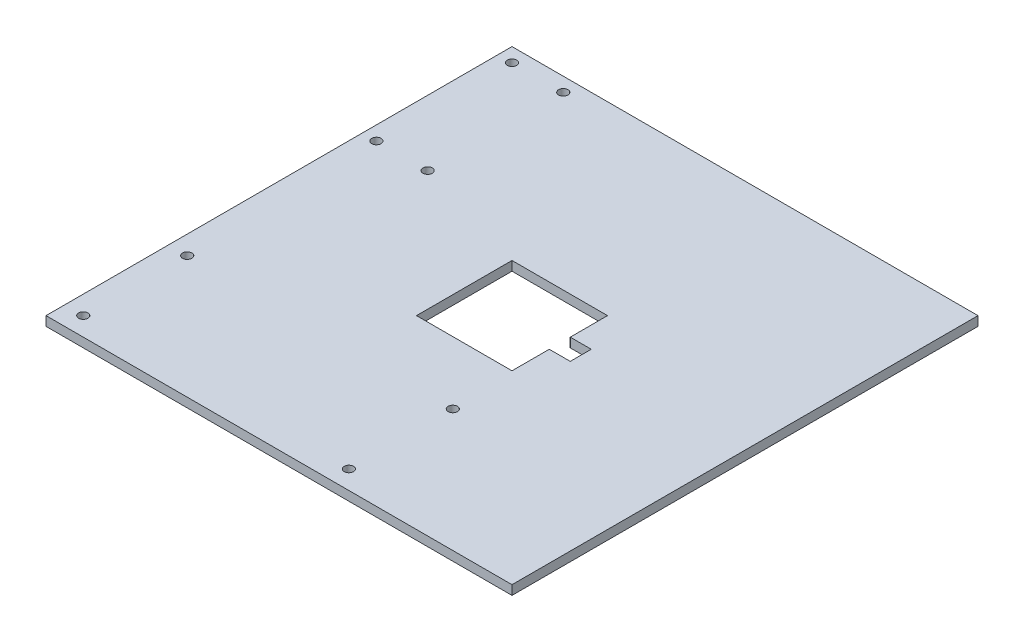
SolidWorks part; units mm, degrees
ref_plane "Front Plane" through (0, 0, 0) normal (0, 0, 1) x (1, 0, 0)
ref_plane "Top Plane" through (0, 0, 0) normal (0, 1, 0) x (1, 0, 0)
ref_plane "Right Plane" through (0, 0, 0) normal (1, 0, 0) x (0, 0, -1)
sketch "Sketch1" plane through (0, 0, 0) normal (0, 1, 0) x (1, 0, 0)
  line L1 (0, 0) -> (100, 0)
  line L2 (0, 0) -> (0, 100)
  line L3 (0, 100) -> (100, 100)
  line L4 (100, 0) -> (100, 100)
  dimension "D1" = 100
  dimension "D2" = 100
extrude "Boss-Extrude1" add sketch "Sketch1" along normal blind 2
sketch "Alignment sketch" plane through (0, 2, 0) normal (0, 1, 0) x (1, 0, 0)
  line L0 (50, 100) -> (50, 0) construction
  line L1 (100, 100) -> (0, 100) construction
  line L2 (0, 0) -> (100, 0) construction
  line L3 (0, 50) -> (100, 50) construction
  line L4 (0, 100) -> (0, 0) construction
  line L5 (100, 0) -> (100, 100) construction
  line L6 (80, 100) -> (80, 90) construction
  line L11 (0, 30.3) -> (65, 30.3) construction
  line L12 (0, 30.3) -> (0, 0) construction
  line L13 (0, 0) -> (65, 0) construction
  line L14 (65, 30.3) -> (65, 0) construction
  line L15 (17, 64.9) -> (0, 64.9) construction
  line L16 (17, 64.9) -> (17, 100) construction
  line L17 (17, 100) -> (0, 100) construction
  line L18 (0, 64.9) -> (0, 100) construction
  line L19 (80, 90) -> (20, 90) construction
  line L20 (20, 90) -> (20, 100) construction
  circle A0 centre (50, 50) radius 19.5 construction
  text T0 "Raspberry Pi Zero W"
  text T1 "Atheros"
  text T2 "Antenna"
  text T3 "Phone Attachment Zone"
  point P31 (50, 90)
  dimension "D1" = 39
  dimension "D2" = 65
  dimension "D3" = 30.3
  dimension "D4" = 35.1
  dimension "D5" = 17
  dimension "D6" = 60
  dimension "D7" = 10
sketch "Sketch3" plane through (0, 2, 0) normal (0, 1, 0) x (1, 0, 0)
  line L0 (50, 100) -> (50, 0) construction
  line L1 (39.75, 60.25) -> (60.25, 60.25)
  line L2 (39.75, 60.25) -> (39.75, 39.75)
  line L3 (39.75, 39.75) -> (60.25, 39.75)
  line L4 (60.25, 60.25) -> (60.25, 39.75)
  line L5 (0, 50) -> (100, 50) construction
  line L7 (60.25, 47.75) -> (64.75, 47.75)
  line L8 (60.25, 47.75) -> (60.25, 52.25)
  line L9 (60.25, 52.25) -> (64.75, 52.25)
  line L10 (64.75, 47.75) -> (64.75, 52.25)
  point P4 (50, 60.25)
  point P7 (50, 39.75)
  point P8 (39.75, 50)
  point P11 (60.25, 50)
  point P12 (60.25, 50)
  dimension "D1" = 20.5
  dimension "D2" = 20.5
  dimension "D3" = 4.5
  dimension "D4" = 4.5
extrude "Cut - Peg Hole" cut sketch "Sketch3" against normal blind 2 contours L4 L1 L2 L3 | L7 L10 L9 L4
sketch "Sketch4" plane through (0, 2, 0) normal (0, 1, 0) x (1, 0, 0)
  line L0 (0, 30.3) -> (65, 30.3) construction
  line L1 (0, 30.3) -> (0, 0) construction
  line L2 (65, 30.3) -> (65, 0) construction
  line L3 (0, 0) -> (65, 0) construction
  circle A0 centre (4, 26.3) radius 1
  circle A1 centre (4, 4) radius 1
  circle A2 centre (61, 26.3) radius 1
  circle A3 centre (61, 4) radius 1
  dimension "D1" = 2
  dimension "D2" = 2
  dimension "D3" = 2
  dimension "D4" = 2
  dimension "D5" = 4
  dimension "D6" = 4
  dimension "D7" = 4
  dimension "D8" = 4
  dimension "D9" = 4
  dimension "D10" = 4
  dimension "D11" = 4
  dimension "D12" = 4
extrude "Cut - Raspberry Pi Screw Holes" cut sketch "Sketch4" against normal blind 2
sketch "Sketch5" plane through (0, 2, 0) normal (0, 1, 0) x (1, 0, 0)
  line L0 (17, 64.9) -> (17, 100) construction
  line L1 (17, 100) -> (0, 100) construction
  line L2 (0, 64.9) -> (0, 100) construction
  line L3 (17, 64.9) -> (0, 64.9) construction
  circle A0 centre (3, 67.9) radius 1
  circle A1 centre (14, 67.9) radius 1
  circle A2 centre (14, 97) radius 1
  circle A3 centre (3, 97) radius 1
  dimension "D1" = 2
  dimension "D2" = 2
  dimension "D3" = 2
  dimension "D4" = 2
  dimension "D5" = 3
  dimension "D6" = 3
  dimension "D7" = 3
  dimension "D8" = 3
  dimension "D9" = 3
  dimension "D10" = 3
  dimension "D11" = 3
  dimension "D12" = 3
extrude "Cut - Atheros Screw Holes" cut sketch "Sketch5" against normal blind 2
